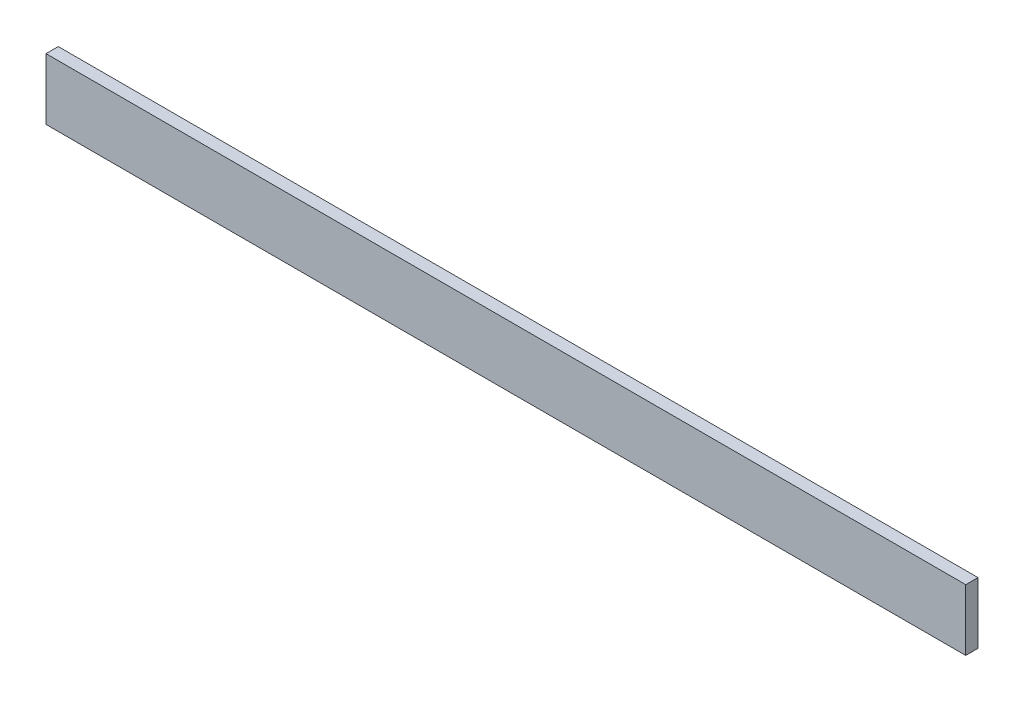
SolidWorks part; units mm, degrees
ref_plane "前视基准面" through (0, 0, 0) normal (0, 0, 1) x (1, 0, 0)
ref_plane "上视基准面" through (0, 0, 0) normal (0, 1, 0) x (1, 0, 0)
ref_plane "右视基准面" through (0, 0, 0) normal (1, 0, 0) x (0, 0, -1)
sketch "草图1" plane through (0, 0, 0) normal (0, 0, 1) x (1, 0, 0)
  line L0 (0, 0) -> (75, 0)
  line L1 (75, 0) -> (75, 5)
  line L2 (75, 5) -> (0, 5)
  line L3 (0, 5) -> (0, 0)
  dimension "D1" = 75
  dimension "D2" = 5
extrude "凸台-拉伸1" add sketch "草图1" along normal blind 1
